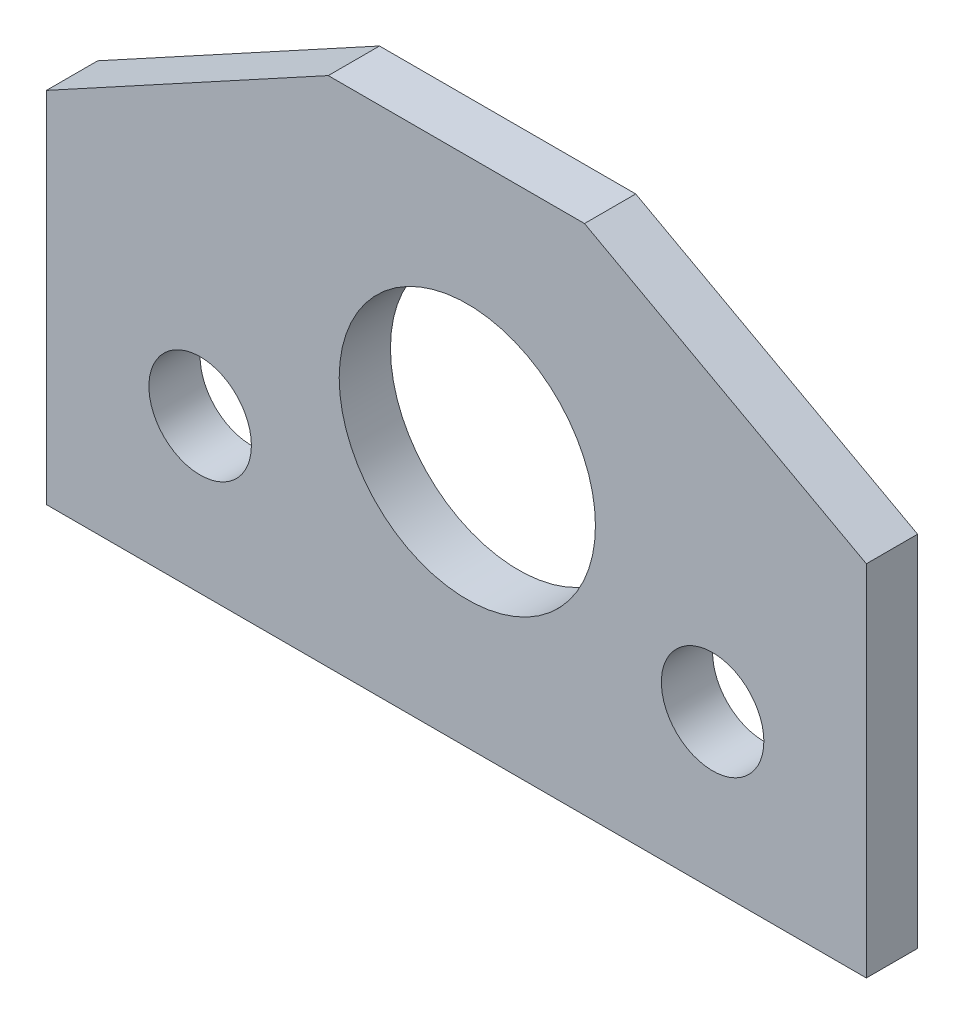
SolidWorks part; units mm, degrees
ref_plane "Front Plane" through (0, 0, 0) normal (0, 0, 1) x (1, 0, 0)
ref_plane "Top Plane" through (0, 0, 0) normal (0, 1, 0) x (1, 0, 0)
ref_plane "Right Plane" through (0, 0, 0) normal (1, 0, 0) x (0, 0, -1)
sketch "Sketch1" plane through (0, 0, 0) normal (0, 0, 1) x (1, 0, 0)
  line L0 (-65.6675, 38.2069) -> (-33.9175, 38.2069)
  line L1 (-33.9175, 38.2069) -> (1.0075, 19.1569)
  line L2 (1.0075, 19.1569) -> (1.0075, -25.2931)
  line L3 (1.0075, -25.2931) -> (-100.5925, -25.2931)
  line L4 (-100.5925, -25.2931) -> (-100.5925, 19.1569)
  line L5 (-100.5925, 19.1569) -> (-65.6675, 38.2069)
  dimension "D1" = 31.75
  dimension "D2" = 44.45
  dimension "D3" = 63.5
  dimension "D4" = 44.45
  dimension "D5" = 101.6
  dimension "D6" = 34.925
extrude "Boss-Extrude1" add sketch "Sketch1" along normal blind 6.35 contours L5 L0 L1 L2 L3 L4
sketch "Sketch2" plane through (0, 0, 6.35) normal (0, 0, 1) x (1, 0, 0)
  line L0 (1.0075, -25.2931) -> (-100.5925, -25.2931) construction
  line L1 (-100.5925, -25.2931) -> (-100.5925, 19.1569) construction
  line L2 (1.0075, 19.1569) -> (1.0075, -25.2931) construction
  circle A0 centre (-81.5425, -6.2431) radius 6.35
  circle A1 centre (-48.4372, 6.4569) radius 15.875
  circle A2 centre (-18.0425, -6.2431) radius 6.35
  point P14 (1.0075, -7.8545)
  dimension "D1" = 12.7
  dimension "D4" = 12.7
  dimension "D7" = 31.75
  dimension "D2" = 19.05
  dimension "D3" = 19.05
  dimension "D5" = 19.05
  dimension "D6" = 19.05
  dimension "D8" = 31.75
extrude "Cut-Extrude1" cut sketch "Sketch2" against normal through all
